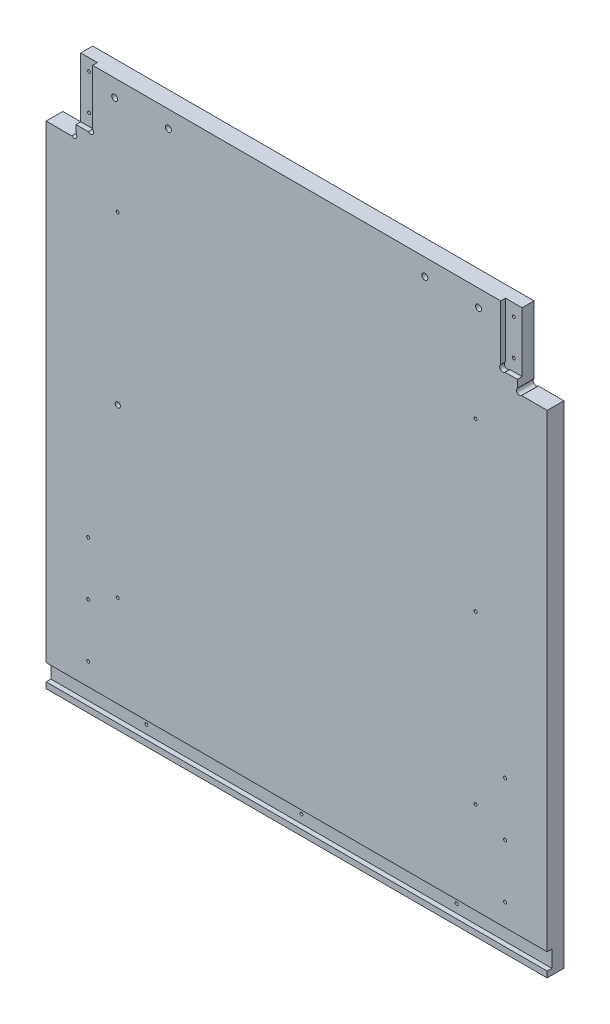
SolidWorks part; units mm, degrees
material "Pine"
ref_plane "Front Plane" through (0, 0, 0) normal (0, 0, 1) x (1, 0, 0)
ref_plane "Top Plane" through (0, 0, 0) normal (0, 1, 0) x (1, 0, 0)
ref_plane "Right Plane" through (0, 0, 0) normal (1, 0, 0) x (0, 0, -1)
sketch "Sketch1" plane through (0, 0, 0) normal (0, 0, 1) x (1, 0, 0)
  line L0 (8932.6508, -5243.5125) -> (10226.1458, -5243.5125)
  line L1 (9086.3208, -4722.0918) -> (10222.9708, -4853.7812)
  line L2 (8914.8708, -6342.0625) -> (10197.5708, -6342.0625)
  line L3 (8914.8708, -5808.6625) -> (10197.5708, -5808.6625)
  line L4 (8919.6333, -5253.0375) -> (10218.2083, -5253.0375)
  line L5 (9134.2633, -4656.1375) -> (9134.2633, -4638.3575)
  line L6 (9091.0833, -4638.3575) -> (9134.2633, -4638.3575)
  line L7 (9091.0833, -4567.2375) -> (9091.0833, -4638.3575)
  line L8 (9134.2633, -4656.1375) -> (9581.3033, -4656.1375)
  line L9 (9091.0833, -4567.2375) -> (9624.4833, -4567.2375)
  line L10 (9581.3033, -4656.1375) -> (9581.3033, -4638.3575)
  line L11 (9581.3033, -4638.3575) -> (9624.4833, -4638.3575)
  line L12 (9624.4833, -4567.2375) -> (9624.4833, -4638.3575)
  line L13 (8932.6508, -5225.7325) -> (9344.9775, -5225.7325)
  line L14 (8932.6508, -5256.2125) -> (8932.6508, -5243.5125)
  line L15 (8911.6958, -5256.2125) -> (8932.6508, -5256.2125)
  line L16 (8914.8708, -4722.0918) -> (9086.3208, -4722.0918)
  line L17 (8911.6958, -4715.5913) -> (8932.6508, -4715.5913)
  line L18 (8914.8708, -6342.0625) -> (8914.8708, -5808.6625)
  line L19 (12082.9917, -4722.0918) -> (10946.3417, -4853.7812)
  line L20 (12236.6617, -5243.5125) -> (10943.1667, -5243.5125)
  line L21 (10951.1042, -5253.0375) -> (12249.6792, -5253.0375)
  line L22 (10838.3917, -5656.2625) -> (11308.2917, -5656.2625)
  line L23 (10838.3917, -5719.7625) -> (11308.2917, -5719.7625)
  line L24 (10838.3917, -5742.5368) -> (11308.2917, -5742.5368)
  line L25 (10806.6417, -6342.0625) -> (11340.0417, -6342.0625)
  line L26 (10803.4667, -6335.7125) -> (11343.2167, -6335.7125)
  line L27 (10803.4667, -6317.9325) -> (11343.2167, -6317.9325)
  line L28 (10943.1667, -5225.7325) -> (11376.4483, -5225.7325)
  line L29 (11506.7292, -4754.5625) -> (10806.6417, -4827.5875)
  line L30 (11506.7292, -4567.2375) -> (11506.7292, -4754.5625)
  line L31 (10806.6417, -4567.2375) -> (10806.6417, -4827.5875)
  line L32 (10806.6417, -4567.2375) -> (11506.7292, -4567.2375)
  line L33 (10235.6708, -6329.3625) -> (10245.1958, -6329.3625)
  line L34 (10245.1958, -6329.3625) -> (10254.7208, -6278.5625)
  line L35 (10302.3458, -6329.3625) -> (10311.8708, -6278.5625)
  line L36 (10302.3458, -6329.3625) -> (10292.8208, -6329.3625)
  line L37 (10245.1958, -5821.3625) -> (10254.7208, -5872.1625)
  line L38 (10235.6708, -5821.3625) -> (10245.1958, -5821.3625)
  line L39 (10292.8208, -5821.3625) -> (10302.3458, -5821.3625)
  line L40 (10302.3458, -5821.3625) -> (10311.8708, -5872.1625)
  line L41 (10235.6708, -5821.3625) -> (10235.6708, -6329.3625)
  line L42 (10254.7208, -5872.1625) -> (10254.7208, -6278.5625)
  line L43 (10311.8708, -5872.1625) -> (10311.8708, -6278.5625)
  line L44 (10292.8208, -5821.3625) -> (10292.8208, -6329.3625)
  line L45 (8932.6508, -5225.7325) -> (8932.6508, -4715.5913)
  line L46 (8911.6958, -4715.5913) -> (8911.6958, -5256.2125)
  line L47 (8914.8708, -5248.275) -> (8914.8708, -4722.0918)
  line L48 (8919.6333, -5253.0375) -> (8914.8708, -5248.275)
  line L49 (8914.8708, -5145.0875) -> (8937.426, -5145.0875)
  line L50 (8914.8708, -5202.2375) -> (8937.426, -5202.2375)
  line L51 (10838.3917, -5656.2625) -> (10838.3917, -5719.7625)
  line L52 (10832.0417, -5736.1868) -> (10856.1717, -5736.1868)
  line L53 (10806.6417, -6342.0625) -> (10806.6417, -5818.7368)
  line L54 (10832.0417, -5649.9125) -> (10856.1717, -5649.9125)
  line L55 (10832.0417, -5726.1125) -> (10856.1717, -5726.1125)
  line L56 (10806.6417, -5818.7368) -> (10833.9015, -5818.7368)
  line L57 (10832.0417, -5806.0442) -> (10851.6815, -5806.0442)
  line L58 (10856.1717, -5801.5541) -> (10856.1717, -5736.1868)
  line L59 (10838.3917, -5814.2467) -> (10838.3917, -5742.5368)
  line L60 (10832.0417, -5806.0442) -> (10832.0417, -5736.1868)
  line L61 (10803.4667, -6317.9325) -> (10803.4667, -6335.7125)
  line L62 (10197.5708, -5808.6625) -> (10197.5708, -6342.0625)
  line L63 (9762.3842, -6348.4125) -> (9762.3842, -5802.3125)
  line L64 (9780.1642, -6348.4125) -> (9762.3842, -6348.4125)
  line L65 (9780.1642, -5802.3125) -> (9780.1642, -6348.4125)
  line L66 (9762.3842, -5802.3125) -> (9780.1642, -5802.3125)
  line L67 (9332.2775, -6348.4125) -> (9332.2775, -5802.3125)
  line L68 (9332.2775, -6348.4125) -> (9350.0575, -6348.4125)
  line L69 (9350.0575, -5802.3125) -> (9350.0575, -6348.4125)
  line L70 (9332.2775, -5802.3125) -> (9350.0575, -5802.3125)
  line L71 (9993.8374, -6061.075) -> (9993.8374, -6045.2418)
  line L72 (9998.5999, -6065.8375) -> (10014.4331, -6065.8375)
  line L73 (9998.5999, -6084.8875) -> (10014.4331, -6084.8875)
  line L74 (9993.8374, -6105.4832) -> (9993.8374, -6089.65)
  line L75 (9974.7874, -6105.4832) -> (9974.7874, -6089.65)
  line L76 (9954.1917, -6084.8875) -> (9970.0249, -6084.8875)
  line L77 (9974.7874, -6061.075) -> (9974.7874, -6045.2418)
  line L78 (9954.1917, -6065.8375) -> (9970.0249, -6065.8375)
  line L79 (10793.9417, -6237.2875) -> (10816.4969, -6237.2875)
  line L80 (10793.9417, -6294.4375) -> (10816.4969, -6294.4375)
  line L81 (10856.1717, -5649.9125) -> (10856.1717, -5726.1125)
  line L82 (10832.0417, -5726.1125) -> (10832.0417, -5649.9125)
  line L83 (10226.1458, -5225.7325) -> (10226.1458, -5243.5125)
  line L84 (10205.1908, -5257.8) -> (10205.1908, -4844.2499)
  line L85 (10230.9083, -4844.2499) -> (10230.9083, -5257.8)
  line L86 (10205.1908, -5257.8) -> (10230.9083, -5257.8)
  line L87 (10205.1908, -4844.2499) -> (10230.9083, -4844.2499)
  line L88 (10946.3417, -5176.8375) -> (10968.8969, -5176.8375)
  line L89 (9349.4676, -5141.9125) -> (9358.2674, -5141.9125)
  line L90 (10946.3417, -5119.6875) -> (10968.8969, -5119.6875)
  line L91 (9929.011, -4660.9635) -> (10066.0807, -4660.9635)
  line L92 (9929.011, -4678.7435) -> (10066.0807, -4678.7435)
  line L93 (10943.1667, -5225.7325) -> (10943.1667, -5243.5125)
  line L94 (10946.3417, -5248.275) -> (10951.1042, -5253.0375)
  line L95 (10946.3417, -5257.8063) -> (10946.3417, -4849.0188)
  line L96 (10964.1217, -5257.8) -> (10964.1217, -4844.2499)
  line L97 (10938.4042, -4844.2499) -> (10938.4042, -5257.8)
  line L98 (10938.4042, -5257.8) -> (10964.1217, -5257.8)
  line L99 (10964.1217, -4844.2499) -> (10938.4042, -4844.2499)
  line L100 (10344.8908, -4560.8875) -> (10369.0208, -4560.8875)
  line L101 (10344.8908, -4560.8875) -> (10369.0208, -4560.8875)
  line L102 (10800.2917, -4560.8875) -> (10824.4217, -4560.8875)
  line L103 (10200.4156, -5119.6875) -> (10222.9708, -5119.6875)
  line L104 (10200.4156, -5176.8375) -> (10222.9708, -5176.8375)
  line L105 (9344.9775, -5146.4026) -> (9344.9775, -5225.7325)
  line L106 (10344.8908, -4560.8875) -> (10344.8908, -4833.9375)
  line L107 (9792.8642, -5225.7325) -> (9792.8642, -5146.4026)
  line L108 (9362.7575, -5225.7325) -> (9775.0842, -5225.7325)
  line L109 (9680.3633, -4761.8396) -> (9680.3633, -4559.9604)
  line L110 (9656.2333, -4559.9604) -> (9680.3633, -4559.9604)
  line L111 (9656.2333, -4761.8396) -> (9680.3633, -4761.8396)
  line L112 (9656.2333, -4761.8396) -> (9656.2333, -4559.9604)
  line L113 (9779.5743, -5141.9125) -> (9788.374, -5141.9125)
  line L114 (10070.5708, -4665.4536) -> (10070.5708, -4674.2534)
  line L115 (9924.5208, -4674.2534) -> (9924.5208, -4665.4536)
  line L116 (12127.4417, -6188.3925) -> (12205.5015, -6188.3925)
  line L117 (12209.9917, -6170.6125) -> (12209.9917, -6183.9024)
  line L118 (9792.8642, -5225.7325) -> (10226.1458, -5225.7325)
  line L119 (9662.5833, -4754.5625) -> (10362.6708, -4827.5875)
  line L120 (9662.5833, -4567.2375) -> (9662.5833, -4754.5625)
  line L121 (10362.6708, -4567.2375) -> (10362.6708, -4827.5875)
  line L122 (9662.5833, -4567.2375) -> (10362.6708, -4567.2375)
  line L123 (10824.4217, -4833.9375) -> (10800.2917, -4833.9375)
  line L124 (10800.2917, -4833.9375) -> (10800.2917, -4560.8875)
  line L125 (10824.4217, -4560.8875) -> (10824.4217, -4833.9375)
  line L126 (10344.8908, -4833.9375) -> (10369.0208, -4833.9375)
  line L127 (10369.0208, -4833.9375) -> (10369.0208, -4560.8875)
  line L128 (10222.9708, -5248.275) -> (10218.2083, -5253.0375)
  line L129 (10222.9708, -5257.8063) -> (10222.9708, -4849.0188)
  line L130 (11734.6544, -5701.375) -> (11739.2301, -5701.375)
  line L131 (9362.7575, -5225.7325) -> (9362.7575, -5146.4026)
  line L132 (9775.0842, -5146.4026) -> (9775.0842, -5225.7325)
  line L133 (11761.3864, -5701.375) -> (11756.8282, -5701.375)
  line L134 (11734.6544, -5693.755) -> (11739.2301, -5693.755)
  line L135 (11761.4039, -5693.755) -> (11756.8282, -5693.755)
  line L136 (11734.6544, -5701.375) -> (11739.2301, -5701.375)
  line L137 (11744.3462, -5721.3024) -> (11744.3462, -5706.4179)
  line L138 (11751.7122, -5721.3024) -> (11751.7122, -5706.4179)
  line L139 (11740.0917, -6170.6125) -> (11740.0917, -6183.9024)
  line L140 (11689.2917, -6188.3925) -> (11822.6417, -6188.3925)
  line L141 (11689.2917, -6348.4093) -> (11689.2917, -6164.2657)
  line L142 (11689.2917, -6164.2657) -> (11746.4417, -6164.2657)
  line L143 (11746.4417, -6164.2657) -> (11746.4417, -6188.3925)
  line L144 (11689.2917, -6164.2657) -> (11746.4417, -6164.2657)
  line L145 (11340.0417, -5818.7368) -> (11340.0417, -6342.0625)
  line L146 (11290.5117, -5726.1125) -> (11314.6417, -5726.1125)
  line L147 (11290.5117, -5649.9125) -> (11290.5117, -5726.1125)
  line L148 (11340.0417, -5818.7368) -> (11312.7818, -5818.7368)
  line L149 (11314.6417, -5806.0442) -> (11295.0018, -5806.0442)
  line L150 (11290.5117, -5801.5541) -> (11290.5117, -5736.1868)
  line L151 (11308.2917, -5814.2467) -> (11308.2917, -5742.5368)
  line L152 (11314.6417, -5806.0442) -> (11314.6417, -5736.1868)
  line L153 (11290.5117, -5736.1868) -> (11314.6417, -5736.1868)
  line L154 (11848.0417, -6267.1325) -> (11962.3417, -6267.1325)
  line L155 (11962.3417, -6267.1325) -> (11962.3417, -6203.6325)
  line L156 (11343.2167, -6317.9325) -> (11343.2167, -6335.7125)
  line L157 (11365.4417, -5656.2625) -> (11365.4417, -5719.7625)
  line L158 (11365.4417, -5656.2625) -> (11479.7417, -5656.2625)
  line L159 (11778.1917, -6071.3937) -> (11802.3217, -6071.3937)
  line L160 (11314.6417, -5726.1125) -> (11314.6417, -5649.9125)
  line L161 (11314.6417, -5649.9125) -> (11290.5117, -5649.9125)
  line L162 (11308.2917, -5719.7625) -> (11308.2917, -5656.2625)
  line L163 (11689.2917, -6348.4093) -> (11713.4217, -6348.4093)
  line L164 (12203.6417, -6164.2657) -> (12260.7917, -6164.2657)
  line L165 (11713.4217, -6348.4093) -> (11713.4217, -6164.2657)
  line L166 (11695.6417, -6342.0625) -> (11695.6417, -6170.6125)
  line L167 (11695.6417, -6048.5337) -> (11699.4517, -6052.3437)
  line L168 (11822.6417, -6292.5325) -> (11822.6417, -6188.3925)
  line L169 (11695.6417, -6342.0625) -> (11695.6417, -6170.6125)
  line L170 (11848.0417, -6203.6325) -> (11962.3417, -6203.6325)
  line L171 (11848.0417, -6203.6325) -> (11848.0417, -6267.1325)
  line L172 (11987.7417, -6267.1325) -> (11987.7417, -6203.6325)
  line L173 (11784.5417, -6077.7437) -> (11784.5417, -6141.2438)
  line L174 (11517.8417, -5656.2625) -> (11632.1417, -5656.2625)
  line L175 (11632.1417, -5656.2625) -> (11632.1417, -5719.7625)
  line L176 (11632.1417, -5719.7625) -> (11517.8417, -5719.7625)
  line L177 (11517.8417, -5719.7625) -> (11517.8417, -5656.2625)
  line L178 (11692.4667, -6028.2137) -> (11692.4667, -6045.9937)
  line L179 (11695.6417, -5979.3188) -> (11718.1969, -5979.3188)
  line L180 (11695.6417, -5922.1687) -> (11718.1969, -5922.1687)
  line L181 (11821.0415, -5722.9375) -> (11821.0415, -5943.6)
  line L182 (11687.7042, -5651.5) -> (11701.9917, -5651.5)
  line L183 (11687.7042, -5651.5) -> (11687.7042, -6055.5251)
  line L184 (11687.7042, -6055.5251) -> (11701.9917, -6055.5251)
  line L185 (11701.9917, -6055.5251) -> (11701.9917, -5651.5)
  line L186 (11695.6417, -6055.2013) -> (11695.6417, -5649.595)
  line L187 (11695.6417, -5656.2625) -> (11695.6417, -6048.5337)
  line L188 (11695.6417, -6170.6125) -> (11740.0917, -6170.6125)
  line L189 (12203.6417, -6164.2657) -> (12203.6417, -6188.3925)
  line L190 (12254.4417, -6342.0625) -> (12254.4417, -6170.6125)
  line L191 (12129.0419, -5943.6) -> (12129.0419, -5722.9375)
  line L192 (12254.4417, -6048.5337) -> (12250.6317, -6052.3437)
  line L193 (12257.6167, -6045.9937) -> (12257.6167, -6028.2137)
  line L194 (12248.0917, -5651.5) -> (12262.3792, -5651.5)
  line L195 (12262.3792, -5651.5) -> (12262.3792, -6055.5251)
  line L196 (12262.3792, -6055.5251) -> (12248.0917, -6055.5251)
  line L197 (12248.0917, -6055.5251) -> (12248.0917, -5651.5)
  line L198 (12254.4417, -6141.2438) -> (12254.4417, -6077.7437)
  line L199 (12236.6617, -6164.2657) -> (12260.7917, -6164.2657)
  line L200 (12102.0417, -6267.1325) -> (11987.7417, -6267.1325)
  line L201 (11330.1865, -6237.2875) -> (11352.7417, -6237.2875)
  line L202 (11330.1865, -6294.4375) -> (11352.7417, -6294.4375)
  line L203 (11474.6617, -5851.8425) -> (11492.4417, -5851.8425)
  line L204 (11474.6617, -5808.6625) -> (11474.6617, -5851.8425)
  line L205 (11403.5417, -5808.6625) -> (11474.6617, -5808.6625)
  line L206 (11492.4417, -5851.8425) -> (11492.4417, -6298.8825)
  line L207 (11403.5417, -6342.0625) -> (11403.5417, -5808.6625)
  line L208 (11474.6617, -6298.8825) -> (11492.4417, -6298.8825)
  line L209 (11474.6617, -6342.0625) -> (11474.6617, -6298.8825)
  line L210 (11403.5417, -6342.0625) -> (11474.6617, -6342.0625)
  line L211 (11619.4417, -5851.8425) -> (11601.6617, -5851.8425)
  line L212 (11601.6617, -5808.6625) -> (11601.6617, -5851.8425)
  line L213 (11530.5417, -5808.6625) -> (11601.6617, -5808.6625)
  line L214 (11619.4417, -5851.8425) -> (11619.4417, -6298.8825)
  line L215 (11530.5417, -6342.0625) -> (11530.5417, -5808.6625)
  line L216 (11619.4417, -6298.8825) -> (11601.6617, -6298.8825)
  line L217 (11601.6617, -6342.0625) -> (11601.6617, -6298.8825)
  line L218 (11530.5417, -6342.0625) -> (11601.6617, -6342.0625)
  line L219 (11479.7417, -5719.7625) -> (11479.7417, -5656.2625)
  line L220 (11365.4417, -5719.7625) -> (11479.7417, -5719.7625)
  line L221 (11778.1917, -6147.5937) -> (11802.3217, -6147.5937)
  line L222 (11802.3217, -6071.3937) -> (11802.3217, -6147.5937)
  line L223 (11778.1917, -6147.5937) -> (11778.1917, -6071.3937)
  line L224 (12254.4417, -5922.1687) -> (12231.8865, -5922.1687)
  line L225 (12254.4417, -5979.3188) -> (12231.8865, -5979.3188)
  line L226 (12254.4417, -6055.2013) -> (12254.4417, -5649.595)
  line L227 (12254.4417, -6048.5337) -> (12254.4417, -5656.2625)
  line L228 (11841.6917, -5702.2873) -> (12108.3917, -5702.2873)
  line L229 (11822.6417, -6292.5325) -> (12127.4417, -6292.5325)
  line L230 (12127.4417, -6292.5325) -> (12127.4417, -6188.3925)
  line L231 (12254.4417, -6170.6125) -> (12209.9917, -6170.6125)
  line L232 (11695.6417, -6342.0625) -> (12254.4417, -6342.0625)
  line L233 (12236.6617, -6348.4093) -> (12260.7917, -6348.4093)
  line L234 (12260.7917, -6348.4093) -> (12260.7917, -6164.2657)
  line L235 (12236.6617, -6348.4093) -> (12236.6617, -6164.2657)
  line L236 (12102.0417, -6203.6325) -> (12102.0417, -6267.1325)
  line L237 (11987.7417, -6203.6325) -> (12102.0417, -6203.6325)
  line L238 (12236.6617, -6147.5937) -> (12236.6617, -6071.3937)
  line L239 (12203.6417, -6188.3925) -> (12260.7917, -6188.3925)
  line L240 (11098.7417, -4665.4536) -> (11098.7417, -4674.2534)
  line L241 (11394.2283, -5146.4026) -> (11394.2283, -5225.7325)
  line L242 (11376.4483, -5225.7325) -> (11376.4483, -5146.4026)
  line L243 (11394.2283, -5225.7325) -> (11806.555, -5225.7325)
  line L244 (11841.6917, -5964.2502) -> (12108.3917, -5964.2502)
  line L245 (12236.6617, -6147.5937) -> (12260.7917, -6147.5937)
  line L246 (12236.6617, -5256.2125) -> (12236.6617, -5243.5125)
  line L247 (12260.7917, -6147.5937) -> (12260.7917, -6071.3937)
  line L248 (12260.7917, -6071.3937) -> (12236.6617, -6071.3937)
  line L249 (12254.4417, -6077.7437) -> (11784.5417, -6077.7437)
  line L250 (11784.5417, -6141.2438) -> (12254.4417, -6141.2438)
  line L252 (12254.4417, -5656.2625) -> (11695.6417, -5656.2625)
  line L253 (11699.4517, -6052.3437) -> (12250.6317, -6052.3437)
  line L254 (11692.4667, -6045.9937) -> (12257.6167, -6045.9937)
  line L255 (11692.4667, -6028.2137) -> (12257.6167, -6028.2137)
  line L256 (11824.335, -5146.4026) -> (11824.335, -5225.7325)
  line L257 (11811.0451, -5141.9125) -> (11819.8449, -5141.9125)
  line L258 (11244.7917, -4674.2534) -> (11244.7917, -4665.4536)
  line L259 (11806.555, -5225.7325) -> (11806.555, -5146.4026)
  line L260 (11488.9492, -4761.8396) -> (11488.9492, -4559.9604)
  line L261 (11488.9492, -4559.9604) -> (11513.0792, -4559.9604)
  line L262 (11488.9492, -4761.8396) -> (11513.0792, -4761.8396)
  line L263 (11513.0792, -4761.8396) -> (11513.0792, -4559.9604)
  line L264 (11240.3015, -4660.9635) -> (11103.2318, -4660.9635)
  line L265 (11103.2318, -4678.7435) -> (11240.3015, -4678.7435)
  line L266 (12236.6617, -5225.7325) -> (12236.6617, -4715.5913)
  line L267 (12257.6167, -4715.5913) -> (12257.6167, -5256.2125)
  line L268 (12254.4417, -5248.275) -> (12254.4417, -4722.0918)
  line L269 (12236.6617, -5225.7325) -> (11824.335, -5225.7325)
  line L270 (12035.0492, -4656.1375) -> (12035.0492, -4638.3575)
  line L271 (12078.2292, -4638.3575) -> (12035.0492, -4638.3575)
  line L272 (12078.2292, -4567.2375) -> (12078.2292, -4638.3575)
  line L273 (12035.0492, -4656.1375) -> (11588.0092, -4656.1375)
  line L274 (11544.8292, -4567.2375) -> (12078.2292, -4567.2375)
  line L275 (11588.0092, -4656.1375) -> (11588.0092, -4638.3575)
  line L276 (11544.8292, -4638.3575) -> (11588.0092, -4638.3575)
  line L277 (11544.8292, -4567.2375) -> (11544.8292, -4638.3575)
  line L278 (12249.6792, -5253.0375) -> (12254.4417, -5248.275)
  line L280 (12257.6167, -5256.2125) -> (12236.6617, -5256.2125)
  line L281 (12231.8865, -5145.0875) -> (12254.4417, -5145.0875)
  line L282 (12231.8865, -5202.2375) -> (12254.4417, -5202.2375)
  line L283 (12236.6617, -4715.5913) -> (12257.6167, -4715.5913)
  line L284 (12082.9917, -4722.0918) -> (12254.4417, -4722.0918)
  line L285 (11380.9385, -5141.9125) -> (11389.7382, -5141.9125)
  circle A0 centre (8923.7608, -4778.9042) radius 1.5875
  circle A1 centre (9062.6598, -4736.3765) radius 2.3685
  circle A2 centre (9051.3958, -6281.7375) radius 22.225
  circle A3 centre (9083.1458, -6249.9875) radius 1.5875
  circle A4 centre (9083.1458, -6313.4875) radius 1.5875
  circle A5 centre (9019.6458, -6249.9875) radius 1.5875
  circle A6 centre (9019.6458, -6313.4875) radius 1.5875
  circle A7 centre (8972.3383, -5202.2375) radius 1.5875
  circle A8 centre (8923.7608, -5015.9708) radius 1.5875
  circle A9 centre (8923.7608, -5134.5042) radius 1.5875
  circle A10 centre (9054.5708, -5234.6225) radius 1.5875
  circle A11 centre (8923.7608, -4897.4375) radius 1.5875
  circle A12 centre (8972.3383, -5087.9375) radius 1.5875
  circle A13 centre (8972.3383, -5145.0875) radius 1.5875
  circle A14 centre (10847.2817, -5668.9625) radius 1.5875
  circle A15 centre (10847.2817, -5707.0625) radius 1.5875
  circle A16 centre (10847.2817, -5755.2368) radius 1.5875
  circle A17 centre (10851.4092, -6237.2875) radius 1.5875
  circle A18 centre (10851.4092, -6294.4375) radius 1.5875
  circle A19 centre (10847.2817, -5793.3442) radius 1.5875
  arc A20 (10833.9015, -5818.7368) -> (10838.3917, -5814.2467) centre (10836.1466, -5816.4918) ccw
  arc A21 (10851.6815, -5806.0442) -> (10856.1717, -5801.5541) centre (10853.9266, -5803.7992) ccw
  circle A22 centre (10882.8417, -6040.4375) radius 1.5875
  circle A23 centre (10882.8417, -6218.2375) radius 1.5875
  circle A24 centre (10882.8417, -5862.6375) radius 1.5875
  circle A25 centre (10908.2417, -6326.8225) radius 1.5875
  circle A26 centre (10908.2417, -6326.8225) radius 1.5875
  circle A27 centre (10851.4092, -6180.1375) radius 1.5875
  circle A28 centre (10815.5317, -4783.4231) radius 1.5875
  circle A29 centre (10815.5317, -4696.9488) radius 1.5875
  circle A30 centre (10815.5317, -4610.4746) radius 1.5875
  circle A31 centre (10979.1323, -4867.0082) radius 2.3685
  circle A32 centre (10190.1802, -4867.0082) radius 2.3685
  circle A33 centre (10955.2317, -4929.9812) radius 1.5875
  circle A34 centre (10955.2317, -5031.5812) radius 1.5875
  circle A35 centre (10214.0808, -4929.9812) radius 1.5875
  circle A36 centre (10214.0808, -5031.5812) radius 1.5875
  circle A37 centre (9341.1675, -6265.8625) radius 1.5875
  circle A38 centre (9771.2742, -5884.8625) radius 1.5875
  circle A39 centre (9771.2742, -6138.8625) radius 1.5875
  circle A40 centre (9771.2742, -6011.8625) radius 1.5875
  arc A41 (10036.2287, -6113.8083) -> (10051.3426, -6111.6033) centre (10042.9639, -6107.0732) ccw
  arc A42 (10051.3426, -6111.6033) -> (10051.3426, -6039.1217) centre (9984.3124, -6075.3625) ccw
  arc A43 (10051.3426, -6039.1217) -> (10036.2287, -6036.9167) centre (10042.9639, -6043.6518) ccw
  arc A44 (10034.5851, -6102.5431) -> (10034.5851, -6048.1819) centre (9984.3124, -6075.3625) ccw
  arc A45 (10034.5851, -6102.5431) -> (10036.2287, -6113.8083) centre (10042.9639, -6107.0732) ccw
  arc A46 (10036.2287, -6036.9167) -> (10034.5851, -6048.1819) centre (10042.9639, -6043.6518) ccw
  arc A47 (9945.8666, -6127.2787) -> (9948.0717, -6142.3927) centre (9952.6018, -6134.0139) ccw
  arc A48 (9948.0717, -6142.3927) -> (10020.5532, -6142.3927) centre (9984.3124, -6075.3625) ccw
  arc A49 (10020.5532, -6142.3927) -> (10022.7583, -6127.2787) centre (10016.0231, -6134.0139) ccw
  arc A50 (9957.1319, -6125.6352) -> (10011.493, -6125.6352) centre (9984.3124, -6075.3625) ccw
  arc A51 (9957.1319, -6125.6352) -> (9945.8666, -6127.2787) centre (9952.6018, -6134.0139) ccw
  arc A52 (10022.7583, -6127.2787) -> (10011.493, -6125.6352) centre (10016.0231, -6134.0139) ccw
  arc A53 (9932.3962, -6036.9167) -> (9917.2822, -6039.1217) centre (9925.661, -6043.6518) ccw
  arc A54 (9917.2822, -6039.1217) -> (9917.2822, -6111.6033) centre (9984.3124, -6075.3625) ccw
  arc A55 (9917.2822, -6111.6033) -> (9932.3962, -6113.8083) centre (9925.661, -6107.0732) ccw
  arc A56 (9934.0398, -6048.1819) -> (9934.0398, -6102.5431) centre (9984.3124, -6075.3625) ccw
  arc A57 (9934.0398, -6048.1819) -> (9932.3962, -6036.9167) centre (9925.661, -6043.6518) ccw
  arc A58 (9932.3962, -6113.8083) -> (9934.0398, -6102.5431) centre (9925.661, -6107.0732) ccw
  arc A59 (9945.8666, -6023.4463) -> (9957.1319, -6025.0898) centre (9952.6018, -6016.7111) ccw
  arc A60 (10011.493, -6025.0898) -> (10022.7583, -6023.4463) centre (10016.0231, -6016.7111) ccw
  arc A61 (10011.493, -6025.0898) -> (9957.1319, -6025.0898) centre (9984.3124, -6075.3625) ccw
  arc A62 (9948.0717, -6008.3323) -> (9945.8666, -6023.4463) centre (9952.6018, -6016.7111) ccw
  arc A63 (10020.5532, -6008.3323) -> (9948.0717, -6008.3323) centre (9984.3124, -6075.3625) ccw
  arc A64 (10022.7583, -6023.4463) -> (10020.5532, -6008.3323) centre (10016.0231, -6016.7111) ccw
  arc A65 (10005.0943, -6187.7574) -> (10096.7073, -6096.1443) centre (9984.3124, -6075.3625) ccw
  arc A66 (9993.8374, -6178.3911) -> (10005.0943, -6187.7574) centre (10003.3624, -6178.3911) ccw
  arc A67 (10001.6306, -6169.0249) -> (10077.9748, -6092.6807) centre (9984.3124, -6075.3625) ccw
  arc A68 (10087.3411, -6084.8875) -> (10077.9748, -6092.6807) centre (10087.3411, -6094.4125) ccw
  arc A69 (10001.6306, -6169.0249) -> (9993.8374, -6178.3911) centre (10003.3624, -6178.3911) ccw
  arc A70 (9963.5306, -6187.7574) -> (9974.7874, -6178.3911) centre (9965.2624, -6178.3911) ccw
  arc A71 (9871.9176, -6096.1443) -> (9963.5306, -6187.7574) centre (9984.3124, -6075.3625) ccw
  arc A72 (9881.2838, -6084.8875) -> (9871.9176, -6096.1443) centre (9881.2838, -6094.4125) ccw
  arc A73 (9890.65, -6092.6807) -> (9966.9943, -6169.0249) centre (9984.3124, -6075.3625) ccw
  arc A74 (9974.7874, -6178.3911) -> (9966.9943, -6169.0249) centre (9965.2624, -6178.3911) ccw
  arc A75 (9890.65, -6092.6807) -> (9881.2838, -6084.8875) centre (9881.2838, -6094.4125) ccw
  arc A76 (9871.9176, -6054.5807) -> (9881.2838, -6065.8375) centre (9881.2838, -6056.3125) ccw
  arc A77 (9963.5306, -5962.9676) -> (9871.9176, -6054.5807) centre (9984.3124, -6075.3625) ccw
  arc A78 (9974.7874, -5972.3339) -> (9963.5306, -5962.9676) centre (9965.2624, -5972.3339) ccw
  arc A79 (9966.9943, -5981.7001) -> (9890.65, -6058.0443) centre (9984.3124, -6075.3625) ccw
  arc A80 (9881.2838, -6065.8375) -> (9890.65, -6058.0443) centre (9881.2838, -6056.3125) ccw
  arc A81 (9966.9943, -5981.7001) -> (9974.7874, -5972.3339) centre (9965.2624, -5972.3339) ccw
  arc A82 (10077.9748, -6058.0443) -> (10087.3411, -6065.8375) centre (10087.3411, -6056.3125) ccw
  arc A83 (9993.8374, -5972.3339) -> (10001.6306, -5981.7001) centre (10003.3624, -5972.3339) ccw
  arc A84 (10077.9748, -6058.0443) -> (10001.6306, -5981.7001) centre (9984.3124, -6075.3625) ccw
  arc A85 (10087.3411, -6065.8375) -> (10096.7073, -6054.5807) centre (10087.3411, -6056.3125) ccw
  arc A86 (10096.7073, -6054.5807) -> (10005.0943, -5962.9676) centre (9984.3124, -6075.3625) ccw
  arc A87 (10005.0943, -5962.9676) -> (9993.8374, -5972.3339) centre (10003.3624, -5972.3339) ccw
  arc A88 (10014.4331, -6065.8375) -> (10018.7361, -6059.0339) centre (10014.4331, -6061.075) ccw
  arc A89 (10018.7361, -6059.0339) -> (10000.641, -6040.9388) centre (9984.3124, -6075.3625) ccw
  arc A90 (10000.641, -6040.9388) -> (9993.8374, -6045.2418) centre (9998.5999, -6045.2418) ccw
  arc A91 (9993.8374, -6061.075) -> (9998.5999, -6065.8375) centre (9998.5999, -6061.075) ccw
  arc A92 (9993.8374, -6105.4832) -> (10000.641, -6109.7862) centre (9998.5999, -6105.4832) ccw
  arc A93 (10000.641, -6109.7862) -> (10018.7361, -6091.6911) centre (9984.3124, -6075.3625) ccw
  arc A94 (10018.7361, -6091.6911) -> (10014.4331, -6084.8875) centre (10014.4331, -6089.65) ccw
  arc A95 (9998.5999, -6084.8875) -> (9993.8374, -6089.65) centre (9998.5999, -6089.65) ccw
  arc A96 (9954.1917, -6084.8875) -> (9949.8888, -6091.6911) centre (9954.1917, -6089.65) ccw
  arc A97 (9949.8888, -6091.6911) -> (9967.9839, -6109.7862) centre (9984.3124, -6075.3625) ccw
  arc A98 (9967.9839, -6109.7862) -> (9974.7874, -6105.4832) centre (9970.0249, -6105.4832) ccw
  arc A99 (9974.7874, -6089.65) -> (9970.0249, -6084.8875) centre (9970.0249, -6089.65) ccw
  arc A100 (9970.0249, -6065.8375) -> (9974.7874, -6061.075) centre (9970.0249, -6061.075) ccw
  arc A101 (9949.8888, -6059.0339) -> (9954.1917, -6065.8375) centre (9954.1917, -6061.075) ccw
  arc A102 (9967.9839, -6040.9388) -> (9949.8888, -6059.0339) centre (9984.3124, -6075.3625) ccw
  arc A103 (9974.7874, -6045.2418) -> (9967.9839, -6040.9388) centre (9970.0249, -6045.2418) ccw
  arc A104 (10096.7073, -6096.1443) -> (10087.3411, -6084.8875) centre (10087.3411, -6094.4125) ccw
  circle A105 centre (9771.2742, -6265.8625) radius 1.5875
  circle A106 centre (9341.1675, -5884.8625) radius 1.5875
  circle A107 centre (9341.1675, -6138.8625) radius 1.5875
  circle A108 centre (9341.1675, -6011.8625) radius 1.5875
  circle A109 centre (11037.2315, -4887.5494) radius 15.0812
  arc A110 (9349.4676, -5141.9125) -> (9344.9775, -5146.4026) centre (9347.2226, -5144.1576) ccw
  arc A111 (9362.7575, -5146.4026) -> (9358.2674, -5141.9125) centre (9360.5124, -5144.1576) ccw
  circle A112 centre (9946.7458, -4669.8535) radius 1.5875
  arc A113 (9924.5208, -4674.2534) -> (9929.011, -4678.7435) centre (9926.7659, -4676.4984) ccw
  circle A114 centre (11003.8092, -5176.8375) radius 1.5875
  circle A115 centre (11003.8092, -5119.6875) radius 1.5875
  circle A116 centre (10353.7808, -4696.9488) radius 1.5875
  circle A117 centre (10353.7808, -4610.4746) radius 1.5875
  circle A118 centre (10353.7808, -4783.4231) radius 1.5875
  circle A119 centre (11003.8092, -5062.5375) radius 1.5875
  circle A120 centre (9353.8675, -5160.9625) radius 1.5875
  circle A121 centre (9638.7708, -5234.6225) radius 1.5875
  circle A122 centre (9671.4733, -4724.1144) radius 1.5875
  circle A123 centre (9671.4733, -4661.3637) radius 1.5875
  circle A124 centre (9671.4733, -4598.6129) radius 1.5875
  arc A125 (9792.8642, -5146.4026) -> (9788.374, -5141.9125) centre (9790.6191, -5144.1576) ccw
  arc A126 (9779.5743, -5141.9125) -> (9775.0842, -5146.4026) centre (9777.3292, -5144.1576) ccw
  circle A127 centre (10048.3458, -4669.8535) radius 1.5875
  arc A128 (10070.5708, -4665.4536) -> (10066.0807, -4660.9635) centre (10068.3258, -4663.2086) ccw
  arc A129 (10066.0807, -4678.7435) -> (10070.5708, -4674.2534) centre (10068.3258, -4676.4984) ccw
  circle A130 centre (9997.5458, -4669.8535) radius 1.5875
  arc A131 (9929.011, -4660.9635) -> (9924.5208, -4665.4536) centre (9926.7659, -4663.2086) ccw
  circle A132 centre (10132.081, -4887.5494) radius 15.0812
  circle A133 centre (10165.5033, -5176.8375) radius 1.5875
  circle A134 centre (10165.5033, -5119.6875) radius 1.5875
  circle A135 centre (9486.3708, -5234.6225) radius 1.5875
  circle A136 centre (10165.5033, -5062.5375) radius 1.5875
  circle A137 centre (9206.9708, -5234.6225) radius 1.5875
  circle A138 centre (10070.5708, -5234.6225) radius 1.5875
  circle A139 centre (9918.1708, -5234.6225) radius 1.5875
  circle A140 centre (9783.9742, -5160.9625) radius 1.5875
  circle A141 centre (9783.9742, -5193.9825) radius 1.5875
  circle A142 centre (9353.8675, -5193.9825) radius 1.5875
  circle A143 centre (11073.3417, -6326.8225) radius 1.5875
  circle A144 centre (11073.3417, -6326.8225) radius 1.5875
  circle A145 centre (11295.2742, -6180.1375) radius 1.5875
  circle A146 centre (11295.2742, -6294.4375) radius 1.5875
  circle A147 centre (11295.2742, -6237.2875) radius 1.5875
  circle A148 centre (11975.0417, -5692.775) radius 3.4925
  circle A149 centre (11263.8417, -5862.6375) radius 1.5875
  arc A150 (11739.2301, -5701.375) -> (11744.3462, -5706.4179) centre (11748.0292, -5697.565) ccw
  arc A151 (11751.7122, -5706.4179) -> (11756.8282, -5701.375) centre (11748.0292, -5697.565) ccw
  arc A152 (11744.3462, -5721.3024) -> (11751.7122, -5721.3024) centre (11748.0292, -5725.505) ccw
  arc A153 (11734.6544, -5693.755) -> (11724.9787, -5697.565) centre (11730.5667, -5697.565) ccw
  arc A154 (11756.8282, -5693.755) -> (11739.2301, -5693.755) centre (11748.0292, -5697.565) ccw
  arc A155 (11724.9787, -5697.565) -> (11734.6544, -5701.375) centre (11730.5667, -5697.565) ccw
  arc A156 (11761.3864, -5701.375) -> (11771.0797, -5697.565) centre (11765.4842, -5697.565) ccw
  arc A157 (11771.0797, -5697.565) -> (11761.4039, -5693.755) centre (11765.4917, -5697.565) ccw
  arc A158 (11740.0917, -6183.9024) -> (11744.5818, -6188.3925) centre (11742.3367, -6186.1474) ccw
  arc A159 (12205.5015, -6188.3925) -> (12209.9917, -6183.9024) centre (12207.7466, -6186.1474) ccw
  circle A160 centre (11299.4017, -5793.3442) radius 1.5875
  arc A161 (11308.2917, -5814.2467) -> (11312.7818, -5818.7368) centre (11310.5367, -5816.4918) ccw
  arc A162 (11290.5117, -5801.5541) -> (11295.0018, -5806.0442) centre (11292.7567, -5803.7992) ccw
  circle A163 centre (11704.5317, -6314.149) radius 1.5875
  circle A164 centre (11748.9817, -6208.7125) radius 1.5875
  circle A165 centre (11263.8417, -6218.2375) radius 1.5875
  circle A166 centre (11263.8417, -6040.4375) radius 1.5875
  circle A167 centre (11238.4417, -6326.8225) radius 1.5875
  circle A168 centre (11238.4417, -6326.8225) radius 1.5875
  circle A169 centre (11299.4017, -5668.9625) radius 1.5875
  circle A170 centre (11299.4017, -5707.0625) radius 1.5875
  circle A171 centre (11726.7567, -6179.5025) radius 1.5875
  circle A172 centre (11704.5317, -6199.3198) radius 1.5875
  circle A173 centre (11748.9817, -6272.2125) radius 1.5875
  circle A174 centre (11704.5317, -6256.7344) radius 1.5875
  circle A175 centre (11299.4017, -5755.2368) radius 1.5875
  circle A176 centre (11913.4467, -6301.4225) radius 1.5875
  circle A177 centre (11790.2567, -6301.4225) radius 1.5875
  circle A178 centre (11793.4317, -6128.5437) radius 1.5875
  circle A179 centre (11753.1092, -5865.0188) radius 1.5875
  circle A180 centre (11809.9417, -6037.1038) radius 1.5875
  circle A181 centre (11809.9417, -6037.1038) radius 1.5875
  circle A182 centre (11753.1092, -5922.1687) radius 1.5875
  circle A183 centre (11975.0417, -5973.7625) radius 3.4925
  circle A184 centre (11975.0417, -6037.1038) radius 1.5875
  circle A185 centre (11753.1092, -5979.3188) radius 1.5875
  circle A186 centre (11975.0417, -6037.1038) radius 1.5875
  arc A187 (11841.6917, -5702.2873) -> (11821.0415, -5722.9375) centre (11841.6917, -5722.9375) ccw
  circle A188 centre (11811.5292, -5833.2687) radius 3.4925
  arc A189 (11821.0415, -5943.6) -> (11841.6917, -5964.2502) centre (11841.6917, -5943.6) ccw
  circle A190 centre (12196.9742, -5865.0188) radius 1.5875
  arc A191 (12129.0419, -5722.9375) -> (12108.3917, -5702.2873) centre (12108.3917, -5722.9375) ccw
  circle A192 centre (12036.6367, -6301.4225) radius 1.5875
  circle A193 centre (12159.8267, -6301.4225) radius 1.5875
  circle A194 centre (12138.5542, -5833.2687) radius 3.4925
  circle A195 centre (12197.2917, -5761.0375) radius 15.0812
  circle A196 centre (11793.4317, -6090.4437) radius 1.5875
  circle A197 centre (12196.9742, -5922.1687) radius 1.5875
  arc A198 (12108.3917, -5964.2502) -> (12129.0419, -5943.6) centre (12108.3917, -5943.6) ccw
  circle A199 centre (12196.9742, -5979.3188) radius 1.5875
  circle A200 centre (12201.1017, -6272.2125) radius 1.5875
  circle A201 centre (12245.5517, -6314.149) radius 1.5875
  circle A202 centre (12245.5517, -6256.7344) radius 1.5875
  circle A203 centre (12201.1017, -6208.7125) radius 1.5875
  circle A204 centre (12223.3267, -6179.5025) radius 1.5875
  circle A205 centre (12245.5517, -6199.3198) radius 1.5875
  circle A206 centre (11171.7667, -4669.8535) radius 1.5875
  circle A207 centre (11222.5667, -4669.8535) radius 1.5875
  arc A208 (11240.3015, -4678.7435) -> (11244.7917, -4674.2534) centre (11242.5466, -4676.4984) ccw
  circle A209 centre (11385.3383, -5193.9825) radius 1.5875
  circle A210 centre (12106.6527, -4736.3765) radius 2.3685
  circle A211 centre (12140.1417, -6037.1038) radius 1.5875
  circle A212 centre (12140.1417, -6037.1038) radius 1.5875
  circle A213 centre (12245.5517, -6090.4437) radius 1.5875
  circle A214 centre (12245.5517, -6128.5437) radius 1.5875
  circle A215 centre (11385.3383, -5160.9625) radius 1.5875
  arc A216 (11824.335, -5146.4026) -> (11819.8449, -5141.9125) centre (11822.0899, -5144.1576) ccw
  arc A217 (11811.0451, -5141.9125) -> (11806.555, -5146.4026) centre (11808.8001, -5144.1576) ccw
  circle A218 centre (11815.445, -5193.9825) radius 1.5875
  circle A219 centre (11815.445, -5160.9625) radius 1.5875
  circle A220 centre (11530.5417, -5234.6225) radius 1.5875
  circle A221 centre (11962.3417, -5234.6225) radius 1.5875
  arc A222 (11244.7917, -4665.4536) -> (11240.3015, -4660.9635) centre (11242.5466, -4663.2086) ccw
  circle A223 centre (11682.9417, -5234.6225) radius 1.5875
  circle A224 centre (11497.8392, -4724.1144) radius 1.5875
  circle A225 centre (11497.8392, -4661.3637) radius 1.5875
  circle A226 centre (11497.8392, -4598.6129) radius 1.5875
  circle A227 centre (11120.9667, -4669.8535) radius 1.5875
  arc A228 (11103.2318, -4660.9635) -> (11098.7417, -4665.4536) centre (11100.9867, -4663.2086) ccw
  arc A229 (11098.7417, -4674.2534) -> (11103.2318, -4678.7435) centre (11100.9867, -4676.4984) ccw
  circle A230 centre (12196.9742, -5202.2375) radius 1.5875
  circle A231 centre (12245.5517, -5015.9708) radius 1.5875
  circle A232 centre (12245.5517, -5134.5042) radius 1.5875
  circle A233 centre (12114.7417, -5234.6225) radius 1.5875
  circle A234 centre (12245.5517, -4897.4375) radius 1.5875
  circle A235 centre (12245.5517, -4778.9042) radius 1.5875
  circle A236 centre (12196.9742, -5087.9375) radius 1.5875
  circle A237 centre (12196.9742, -5145.0875) radius 1.5875
  circle A238 centre (11098.7417, -5234.6225) radius 1.5875
  circle A239 centre (11251.1417, -5234.6225) radius 1.5875
  arc A240 (11380.9385, -5141.9125) -> (11376.4483, -5146.4026) centre (11378.6934, -5144.1576) ccw
  arc A241 (11394.2283, -5146.4026) -> (11389.7382, -5141.9125) centre (11391.9833, -5144.1576) ccw
sketch "Sketch3" plane through (0, 0, 0) normal (0, 0, 1) x (1, 0, 0)
  line L0 (10806.6417, -6342.0625) -> (11340.0417, -6342.0625)
  line L1 (11340.0417, -6342.0625) -> (11340.0417, -5818.7368)
  line L2 (11340.0417, -5818.7368) -> (11308.2917, -5818.7368)
  line L4 (11308.2917, -5818.7368) -> (11308.2917, -5742.5368)
  line L5 (10838.3917, -5742.5368) -> (10838.3917, -5818.7368)
  line L7 (10838.3917, -5818.7368) -> (10806.6417, -5818.7368)
  line L8 (10806.6417, -5818.7368) -> (10806.6417, -6342.0625)
  line L9 (10838.3917, -5742.5368) -> (11308.2917, -5742.5368)
  dimension "D1" = 533.4
  dimension "D2" = 31.75
  dimension "D3" = 31.75
  dimension "D4" = 76.2
extrude "Extrude1" add sketch "Sketch3" against normal blind 17.78
sketch "Sketch4" plane through (0, 0, 0) normal (0, 0, 1) x (1, 0, 0)
  line L0 (10838.3917, -5818.7368) -> (10836.1466, -5816.4918) construction
  line L1 (11308.2917, -5818.7368) -> (11310.5367, -5816.4918) construction
  line L2 (11340.0417, -5818.7368) -> (11308.2917, -5818.7368) construction
  line L3 (10838.3917, -5818.7368) -> (10806.6417, -5818.7368) construction
  circle A0 centre (11310.5367, -5816.4918) radius 3.175
  circle A1 centre (10836.1466, -5816.4918) radius 3.175
  dimension "D1" = 3.175
  dimension "D2" = 45
  dimension "D3" = 3.175
  dimension "D4" = 45
extrude "Cut-Extrude1" cut sketch "Sketch4" against normal up to surface (17.78 mm away) up to face at (11073.3417, -5930.5183, -17.78)
sketch "Sketch6" plane through (0, 0, 0) normal (0, 0, 1) x (1, 0, 0)
  line L0 (11073.3417, -6342.0625) -> (11073.3417, -6326.8225) construction
  line L1 (10806.6417, -6342.0625) -> (11340.0417, -6342.0625) construction
  line L2 (11073.3417, -6326.8225) -> (10908.2417, -6326.8225) construction
  line L3 (11073.3417, -6326.8225) -> (11238.4417, -6326.8225) construction
  line L4 (10847.2817, -5793.3442) -> (10847.2817, -5755.2368) construction
  line L5 (10847.2817, -5755.2368) -> (10847.2817, -5742.5368) construction
  line L6 (11308.2917, -5742.5368) -> (10838.3917, -5742.5368) construction
  line L7 (10847.2817, -5742.5368) -> (10838.3917, -5742.5368) construction
  line L8 (11299.4017, -5793.3442) -> (11299.4017, -5755.2368) construction
  line L9 (11299.4017, -5755.2368) -> (11299.4017, -5742.5368) construction
  line L10 (11299.4017, -5742.5368) -> (11308.2917, -5742.5368) construction
  line L11 (10806.6417, -6342.0625) -> (10806.6417, -5742.5368) construction
  line L12 (10806.6417, -6042.2997) -> (10882.8417, -6042.2997) construction
  line L13 (10882.8417, -5864.4997) -> (10882.8417, -6042.2997) construction
  line L14 (10806.6417, -5742.5368) -> (10838.3917, -5742.5368) construction
  line L15 (10882.8417, -6042.2997) -> (10882.8417, -6220.0997) construction
  line L16 (11340.0417, -6342.0625) -> (11340.0417, -5742.5368) construction
  line L17 (11340.0417, -5742.5368) -> (11308.2917, -5742.5368) construction
  line L18 (11340.0417, -6042.2997) -> (11263.8417, -6042.2997) construction
  line L19 (11263.8417, -5864.4997) -> (11263.8417, -6042.2997) construction
  line L20 (11263.8417, -6042.2997) -> (11263.8417, -6220.0997) construction
  circle A0 centre (10851.4092, -6294.4375) radius 1.5875
  circle A1 centre (10908.2417, -6326.8225) radius 1.5875
  circle A2 centre (11073.3417, -6326.8225) radius 1.5875
  circle A3 centre (11238.4417, -6326.8225) radius 1.5875
  circle A4 centre (11295.2742, -6294.4375) radius 1.5875
  circle A5 centre (11295.2742, -6237.2875) radius 1.5875
  circle A6 centre (11263.8417, -6220.0997) radius 1.5875
  circle A7 centre (11295.2742, -6180.1375) radius 1.5875
  circle A8 centre (11263.8417, -6042.2997) radius 1.5875
  circle A9 centre (11263.8417, -5864.4997) radius 1.5875
  circle A10 centre (11299.4017, -5793.3442) radius 1.5875
  circle A11 centre (11299.4017, -5755.2368) radius 1.5875
  circle A12 centre (10847.2817, -5755.2368) radius 1.5875
  circle A13 centre (10847.2817, -5793.3442) radius 1.5875
  circle A14 centre (10882.8417, -6042.2997) radius 2.7778
  circle A15 centre (10851.4092, -6180.1375) radius 1.5875
  circle A16 centre (10882.8417, -6220.0997) radius 1.5875
  circle A17 centre (10851.4092, -6237.2875) radius 1.5875
  circle A18 centre (10882.8417, -5864.4997) radius 1.5875
  dimension "D1" = 8.89
  dimension "D2" = 8.89
  dimension "D3" = 177.8
  dimension "D4" = 177.8
  dimension "D5" = 76.2
  dimension "D6" = 177.8
  dimension "D7" = 76.2
  dimension "D8" = 177.8
extrude "Cut-Extrude3" cut sketch "Sketch6" against normal up to surface (17.78 mm away) up to face at (11073.3417, -5907.713, -17.78)
sketch "Sketch5" plane through (0, 0, 0) normal (0, 0, 1) x (1, 0, 0)
  line L0 (11073.3417, -6317.9325) -> (11073.3417, -6342.0625) construction
  line L1 (10803.4667, -6317.9325) -> (11343.2167, -6317.9325) construction
  line L2 (10806.6417, -6342.0625) -> (11340.0417, -6342.0625) construction
  line L3 (11073.3417, -6317.9325) -> (10806.6417, -6317.9325)
  line L4 (10838.3917, -5742.5368) -> (10838.3917, -5806.0442)
  line L5 (11340.0417, -6342.0625) -> (11340.0417, -5818.7368) construction
  line L6 (11308.2917, -5742.5368) -> (11308.2917, -5806.0442)
  line L8 (10838.3917, -5806.0442) -> (10856.1717, -5806.0442)
  line L11 (11308.2917, -5806.0442) -> (11290.5117, -5806.0442)
  line L12 (10806.6417, -6342.0625) -> (10806.6417, -5818.7368) construction
  line L13 (10806.6417, -6317.9325) -> (10806.6417, -6335.7125)
  line L15 (10806.6417, -6335.7125) -> (11340.0417, -6335.7125)
  line L17 (10856.1717, -5806.0442) -> (10856.1717, -5742.5368)
  line L20 (10856.1717, -5742.5368) -> (10838.3917, -5742.5368)
  line L21 (11290.5117, -5806.0442) -> (11290.5117, -5742.5368)
  line L24 (11290.5117, -5742.5368) -> (11308.2917, -5742.5368)
  line L26 (11340.0417, -6317.9325) -> (11073.3417, -6317.9325)
  line L27 (11340.0417, -6335.7125) -> (11340.0417, -6317.9325)
  dimension "D1" = 17.78
  dimension "D3" = 17.78
  dimension "D4" = 17.78
extrude "Cut-Extrude2" cut sketch "Sketch5" against normal blind 5.08
sketch "Sketch7" plane through (0, 0, 0) normal (0, 0, 1) x (1, 0, 0)
  line L0 (10856.1717, -5806.0442) -> (10853.9266, -5803.7992) construction
  line L1 (11290.5117, -5806.0442) -> (11292.7567, -5803.7992) construction
  line L2 (10838.3917, -5806.0442) -> (10856.1717, -5806.0442) construction
  line L3 (11290.5117, -5806.0442) -> (11308.2917, -5806.0442) construction
  circle A0 centre (10853.9266, -5803.7992) radius 3.302
  circle A1 centre (11292.7567, -5803.7992) radius 3.302
  dimension "D1" = 45
  dimension "D2" = 3.175
  dimension "D3" = 45
  dimension "D4" = 3.175
extrude "Cut-Extrude4" cut sketch "Sketch7" against normal up to surface (5.08 mm away) up to face at (10848.8692, -5793.3442, -5.08)
sketch "Sketch9" plane through (0, 0, 0) normal (0, 0, 1) x (1, 0, 0)
  circle A0 centre (10879.6167, -5760.6443) radius 3.175
  circle A1 centre (10936.8167, -5760.6443) radius 3.175
  circle A2 centre (11209.8167, -5760.6443) radius 3.175
  circle A3 centre (11267.0167, -5760.6443) radius 3.175
extrude "Cut-Extrude5" cut sketch "Sketch9" against normal up to surface (17.78 mm away) up to face at (10884.4292, -5864.4997, -17.78)
